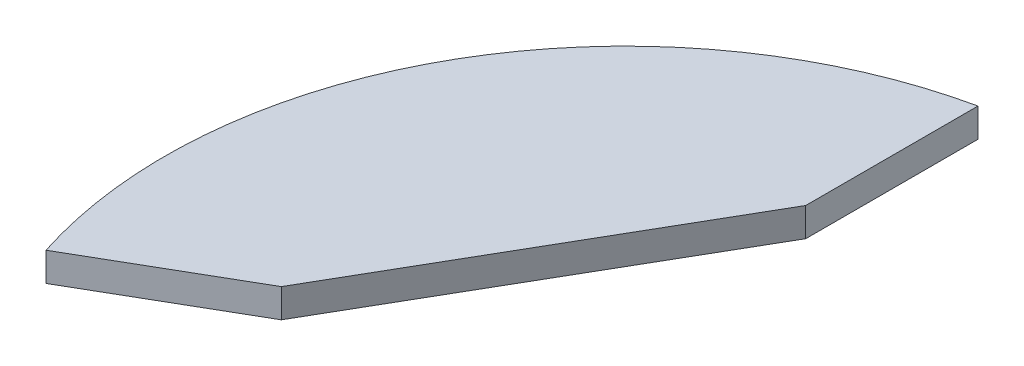
SolidWorks part; units mm, degrees
ref_plane "Front Plane" through (0, 0, 0) normal (0, 0, 1) x (1, 0, 0)
ref_plane "Top Plane" through (0, 0, 0) normal (0, 1, 0) x (1, 0, 0)
ref_plane "Right Plane" through (0, 0, 0) normal (1, 0, 0) x (0, 0, -1)
sketch "Sketch1" plane through (0, 0, 0) normal (0, 1, 0) x (1, 0, 0)
  line L0 (0, 62.0519) -> (0, -57.4298) construction
  line L1 (-10.7442, -6.2032) -> (-43.9941, -25.4) construction
  line L2 (-10.7442, 49.6508) -> (-10.7442, 30.6508)
  line L3 (-31.9165, -6.0207) -> (-48.371, -15.5207)
  line L4 (0, 0) -> (-43.9941, -25.4) construction
  line L5 (-5.3721, 9.3048) -> (-49.3662, -16.0952) construction
  line L6 (-10.7442, 62.0519) -> (-10.7442, -57.4298) construction
  line L7 (-31.9165, -6.0207) -> (-10.7442, 30.6508)
  arc A0 (-10.7442, 49.6508) -> (-48.371, -15.5207) centre (0, 0) ccw
  dimension "D1" = 101.6
  dimension "D2" = 120
  dimension "D5" = 19
  dimension "D6" = 19
  dimension "D3" = 10.7442
  dimension "D4" = 10.7442
extrude "Extrude1" add sketch "Sketch1" along normal blind 3.175
